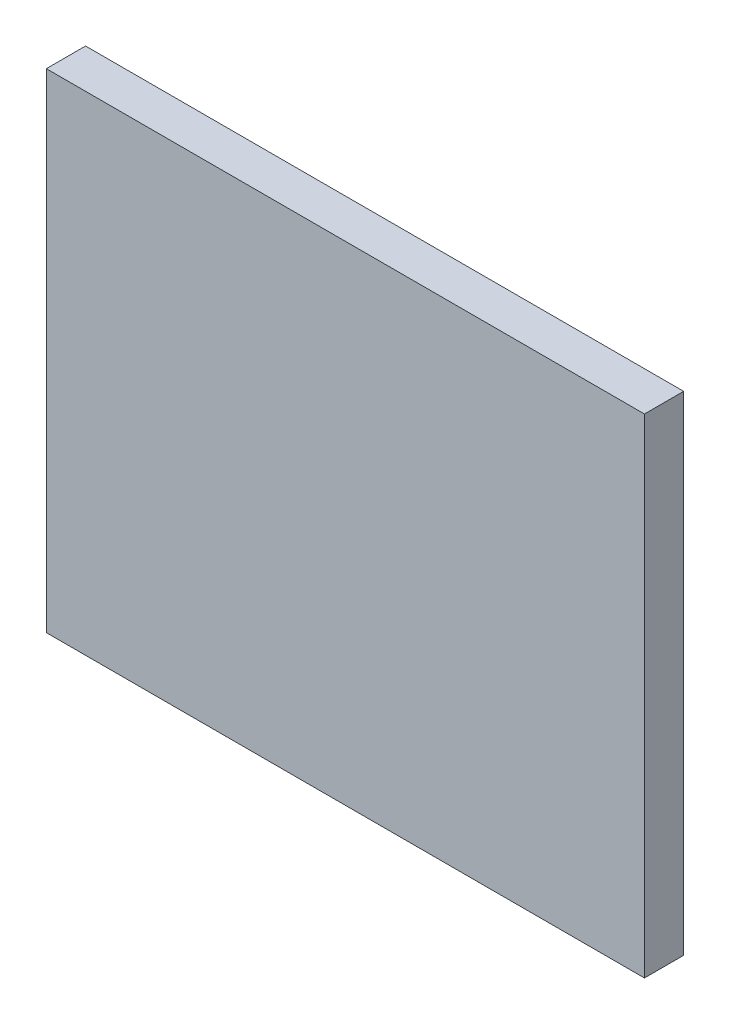
SolidWorks part; units mm, degrees
ref_plane "Ebene vorne" through (0, 0, 0) normal (0, 0, 1) x (1, 0, 0)
ref_plane "Ebene oben" through (0, 0, 0) normal (0, 1, 0) x (1, 0, 0)
ref_plane "Ebene rechts" through (0, 0, 0) normal (1, 0, 0) x (0, 0, -1)
sketch "Skizze1" plane through (0, 0, 0) normal (0, 0, 1) x (1, 0, 0)
  line L0 (-7.62, 10.922) -> (7.62, 10.922)
  line L1 (7.62, 10.922) -> (7.62, -1.524)
  line L2 (7.62, -1.524) -> (-7.62, -1.524)
  line L3 (-7.62, -1.524) -> (-7.62, 10.922)
extrude "Component_Outline" add sketch "Skizze1" along normal blind 1 separate body
sketch3d "3D-Skizze1"
  line L0 (0, 0, 0) -> (1, 0, 0)
  line L1 (0, 0, 0) -> (0, 1, 0)
  line L2 (0, 0, 0) -> (0, 0, 1)
  point P0 (0, 0, 0)
